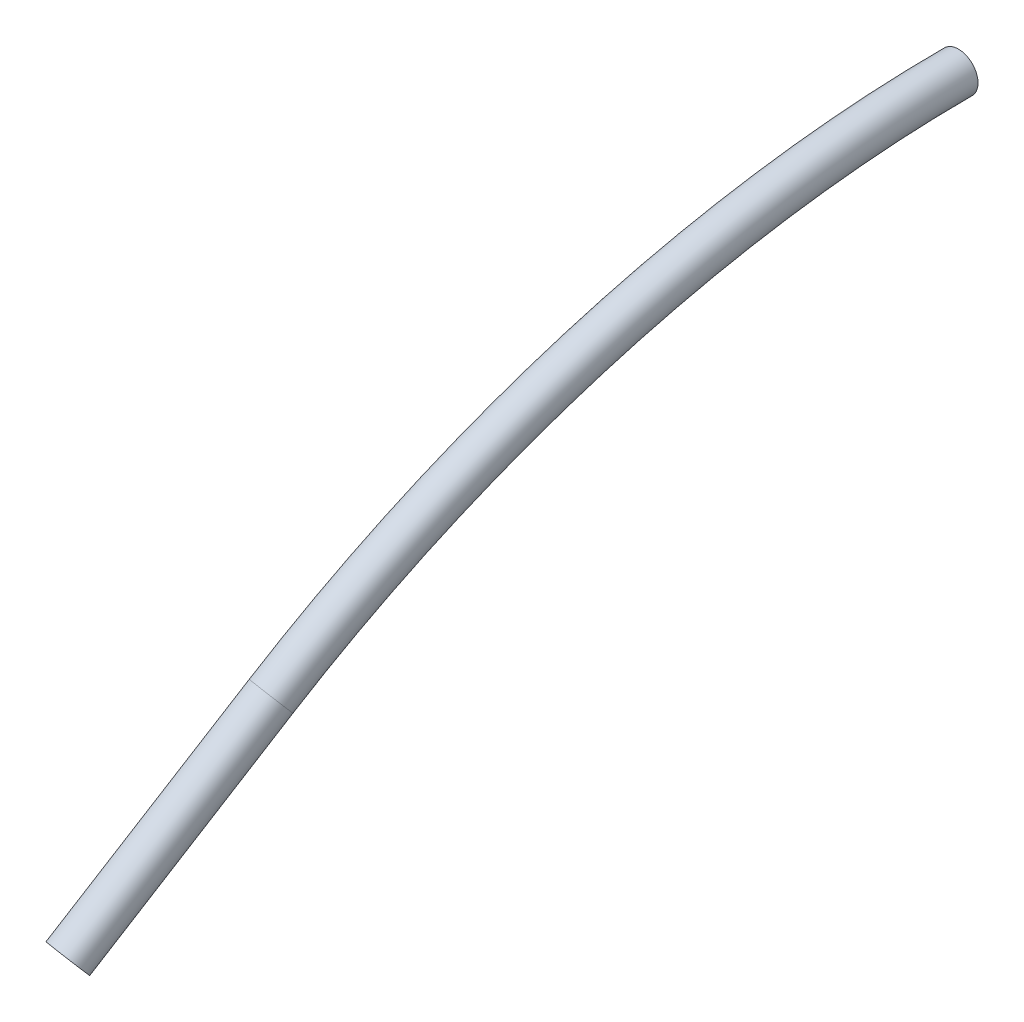
SolidWorks part; units mm, degrees
ref_plane "Front" through (0, 0, 0) normal (0, 0, 1) x (1, 0, 0)
ref_plane "Top" through (0, 0, 0) normal (0, 1, 0) x (1, 0, 0)
ref_plane "Right" through (0, 0, 0) normal (1, 0, 0) x (0, 0, -1)
sketch "Sketch1" plane through (0.0106, -0.0153, 0) normal (0, 0, 1) x (-0.2924, 0.9563, 0)
  circle A0 centre (2324.7464, -4791.7694) radius 50.8
ref_plane "Plane1" through (3153.382, -564.0572, 0) normal (0.9844, -0.1761, 0) x (-0.1699, -0.9498, -0.2627)
sketch "Sketch2" plane through (3153.382, -564.0572, 0) normal (0.9844, -0.1761, 0) x (-0.1699, -0.9498, -0.2627)
  line L0 (-4105.3671, 1117.7896) -> (-4683.639, -1006.0611) construction
  line L1 (-3625.7531, -1206.2199) -> (-3664.241, -1209.8867) construction
  line L2 (-3933.7575, -663.1025) -> (-3664.241, -1209.8867)
  line L3 (-3933.7575, -663.1025) -> (-4105.3671, 1117.7896) construction
  line L4 (-4019.5623, 227.3436) -> (-4182.4687, 211.6456) construction
  arc A0 (-4105.3671, 1117.7896) -> (-3933.7575, -663.1025) centre (-1667.4273, 453.9991) ccw
  dimension "D1" = 1828.8
  dimension "D2" = 609.6
  dimension "D3" = 163.661
sweep "Sweep1" add profiles "Sketch1" path "Sketch2"
ref_plane "Plane2" through (87.5378, 489.383, -562.5147) normal (-0.1166, -0.6519, 0.7493) x (0.9932, -0.0765, 0.088)
